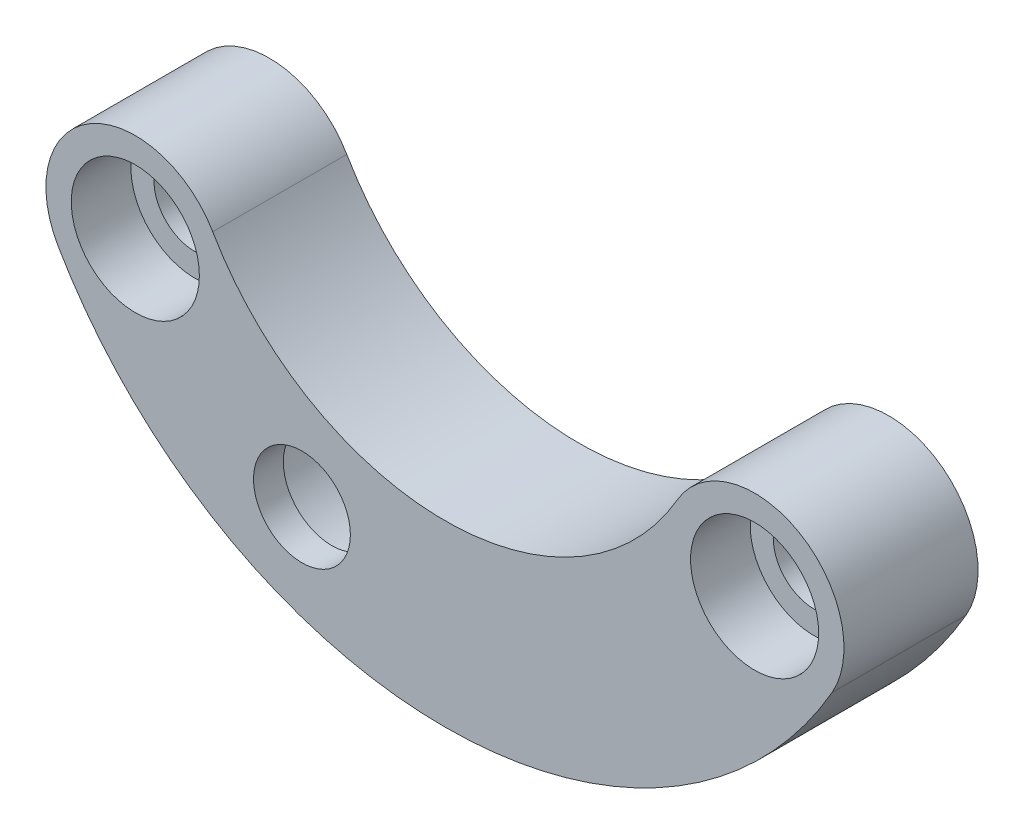
SolidWorks part; units mm, degrees
ref_plane "Plano frontal" through (0, 0, 0) normal (0, 0, 1) x (1, 0, 0)
ref_plane "Plano superior" through (0, 0, 0) normal (0, 1, 0) x (1, 0, 0)
ref_plane "Plano direito" through (0, 0, 0) normal (1, 0, 0) x (0, 0, -1)
sketch "Esboço1" plane through (0, 0, 0) normal (0, 0, 1) x (1, 0, 0)
  line L0 (0, 0) -> (0, -15) construction
  line L1 (-10.3923, -6) -> (0, 0) construction
  line L2 (10.3923, -6) -> (0, 0) construction
  circle A22 centre (-10.3923, -6) radius 1.375
  arc A23 (-7.7942, -4.5) -> (-12.9904, -7.5) centre (-10.3923, -6) ccw
  arc A24 (-7.7942, -4.5) -> (7.7942, -4.5) centre (0, 0) ccw
  arc A25 (-12.9904, -7.5) -> (12.9904, -7.5) centre (0, 0) ccw
  arc A26 (7.7942, -4.5) -> (12.9904, -7.5) centre (10.3923, -6) cw
  circle A27 centre (10.3923, -6) radius 1.375
  dimension "D1" = 12
  dimension "D2" = 60
  dimension "D3" = 2.75
  dimension "D4" = 6
extrude "Ressalto-extrusão3" add sketch "Esboço1" along normal blind 4.5
sketch "Esboço7" plane through (0, 0, 4.5) normal (0, 0, 1) x (1, 0, 0)
  line L0 (0, 0) -> (0, -15) construction
  circle A0 centre (-4.8, -10.9982) radius 1.625
  arc A1 (-12.9904, -7.5) -> (12.9904, -7.5) centre (0, 0) ccw construction
  dimension "D1" = 4.8
  dimension "D2" = 12
  dimension "D3" = 3.25
extrude "Corte-extrusão4" cut sketch "Esboço7" against normal through all
sketch "Esboço8" plane through (0, 0, 4.5) normal (0, 0, 1) x (1, 0, 0)
  circle A0 centre (-10.3923, -6) radius 2.15
  circle A1 centre (10.3923, -6) radius 2.15
  dimension "D1" = 4.3
  dimension "D2" = 4.3
extrude "Corte-extrusão5" cut sketch "Esboço8" against normal blind 2
sketch "Esboço9" plane through (0, 0, 0) normal (0, 0, -1) x (-1, 0, 0)
  circle A0 centre (4.8, -10.9982) radius 2.9
  dimension "D1" = 5.8
extrude "Corte-extrusão6" cut sketch "Esboço9" against normal blind 3.5
